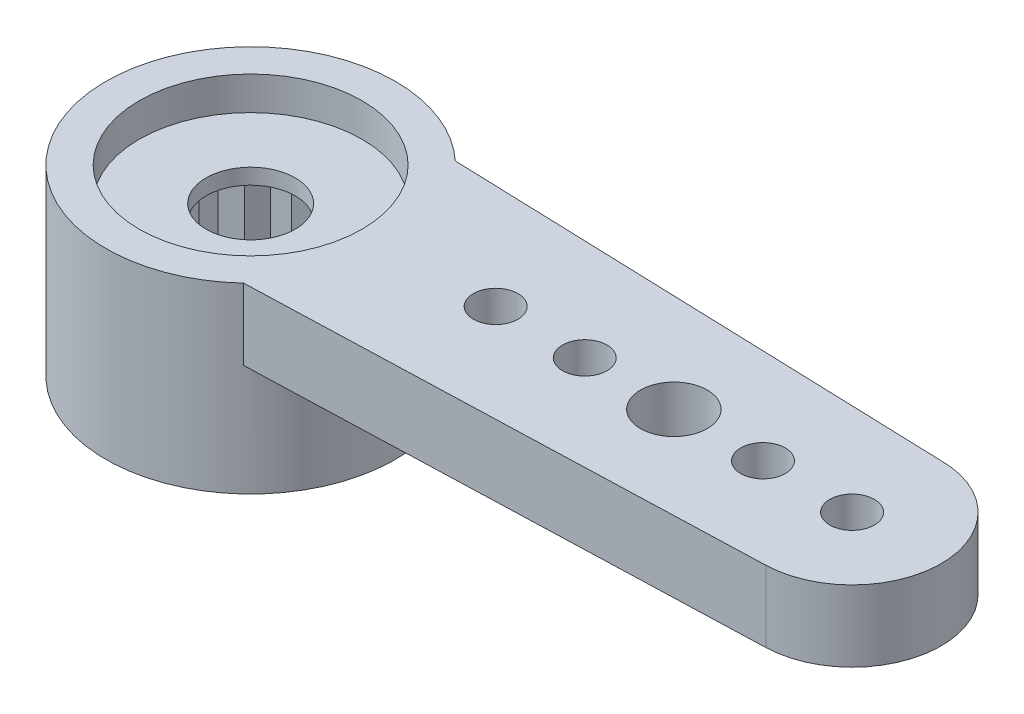
SolidWorks part; units mm, degrees
material "Nylon 101"
ref_plane "Front" through (0, 0, 0) normal (0, 0, 1) x (1, 0, 0)
ref_plane "Top" through (0, 0, 0) normal (0, 1, 0) x (1, 0, 0)
ref_plane "Right" through (0, 0, 0) normal (1, 0, 0) x (0, 0, -1)
sketch "Sketch1" plane through (0, 0, 0) normal (0, 1, 0) x (1, 0, 0)
  line L0 (0, 0) -> (13.5, 0) construction
  line L1 (2.2185, 2.375) -> (13.5, 2)
  line L2 (2.2185, -2.375) -> (13.5662, -1.9989)
  arc A0 (2.2185, 2.375) -> (2.2185, -2.375) centre (0, 0) ccw
  arc A1 (13.5662, -1.9989) -> (13.5, 2) centre (13.5, 0) ccw
  circle A2 centre (13.5, 0) radius 0.5
  circle A5 centre (11.5, 0) radius 0.5
  circle A6 centre (9.5, 0) radius 0.75
  circle A7 centre (7.5, 0) radius 0.5
  circle A8 centre (5.5, 0) radius 0.5
  point P10 (0, 0)
  dimension "D2" = 6.5
  dimension "D3" = 4
  dimension "D4" = 1
  dimension "D8" = 2
  dimension "D5" = 1.5
  dimension "D1" = 13.5
  dimension "D6" = 2
  dimension "D7" = 4.75
  dimension "D9" = 2
  dimension "D10" = 2
extrude "Boss-Extrude1" add sketch "Sketch1" along normal blind 1.6
sketch "Sketch2" plane through (0, 0, 0) normal (0, -1, 0) x (1, 0, 0)
  circle A0 centre (0, 0) radius 3.25
  arc A1 (2.2185, 2.375) -> (2.2185, -2.375) centre (0, 0) ccw construction
extrude "Boss-Extrude2" add sketch "Sketch2" along normal blind 2.5
sketch "Sketch3" plane through (0, 1.6, 0) normal (0, 1, 0) x (1, 0, 0)
  circle A0 centre (0, 0) radius 2.5
  arc A1 (2.2185, 2.375) -> (2.2185, -2.375) centre (0, 0) ccw construction
  dimension "D1" = 0.75
sketch "Sketch4" plane through (0, 1.6, 0) normal (0, 1, 0) x (1, 0, 0)
  circle A0 centre (0, 0) radius 1
  dimension "D1" = 2
extrude "Cut-Extrude1" cut sketch "Sketch4" against normal through all
sketch "Sketch5" plane through (0, -2.5, 0) normal (0, -1, 0) x (1, 0, 0)
  line L0 (0, 0) -> (0, 2.4914) construction
  line L1 (0, 0) -> (0.3742, 1.7607) construction
  line L2 (1.0133, 2.276) -> (0, 0) construction
  line L3 (0, 2) -> (0.3742, 1.7607)
  line L4 (0.3742, 1.7607) -> (0.8135, 1.8271)
  line L5 (0.3742, 1.7607) -> (0.4158, 1.9563) construction
  line L6 (0.8135, 1.8271) -> (1.058, 1.4562)
  line L7 (1.058, 1.4562) -> (1.4863, 1.3383)
  line L8 (1.4863, 1.3383) -> (1.5588, 0.9)
  line L9 (1.5588, 0.9) -> (1.9021, 0.618)
  line L10 (1.9021, 0.618) -> (1.7901, 0.1882)
  line L11 (1.7901, 0.1882) -> (1.989, -0.2091)
  line L12 (1.989, -0.2091) -> (1.7119, -0.5562)
  line L13 (1.7119, -0.5562) -> (1.7321, -1)
  line L14 (1.7321, -1) -> (1.3377, -1.2044)
  line L15 (1.3377, -1.2044) -> (1.1756, -1.618)
  line L16 (1.1756, -1.618) -> (0.7321, -1.6444)
  line L17 (0.7321, -1.6444) -> (0.4158, -1.9563)
  line L18 (0.4158, -1.9563) -> (0, -1.8)
  line L19 (0, -1.8) -> (-0.4158, -1.9563)
  line L20 (-0.4158, -1.9563) -> (-0.7321, -1.6444)
  line L21 (-0.7321, -1.6444) -> (-1.1756, -1.618)
  line L22 (-1.1756, -1.618) -> (-1.3377, -1.2044)
  line L23 (-1.3377, -1.2044) -> (-1.7321, -1)
  line L24 (-1.7321, -1) -> (-1.7119, -0.5562)
  line L25 (-1.7119, -0.5562) -> (-1.989, -0.2091)
  line L26 (-1.989, -0.2091) -> (-1.7901, 0.1882)
  line L27 (-1.7901, 0.1882) -> (-1.9021, 0.618)
  line L28 (-1.9021, 0.618) -> (-1.5588, 0.9)
  line L29 (-1.5588, 0.9) -> (-1.4863, 1.3383)
  line L30 (-1.4863, 1.3383) -> (-1.058, 1.4562)
  line L31 (-1.058, 1.4562) -> (-0.8135, 1.8271)
  line L32 (-0.8135, 1.8271) -> (-0.3742, 1.7607)
  line L33 (-0.3742, 1.7607) -> (0, 2)
  circle A0 centre (0, 0) radius 2 construction
  point P3 (0, 2)
  point P6 (0.8135, 1.8271)
  dimension "D1" = 4
  dimension "D2" = 24
  dimension "D3" = 12
  dimension "D4" = 0.2
  dimension "D5" = 15
extrude "Cut-Extrude2" cut sketch "Sketch5" against normal blind 3
extrude "Cut-Extrude3" cut sketch "Sketch3" against normal blind 0.75
